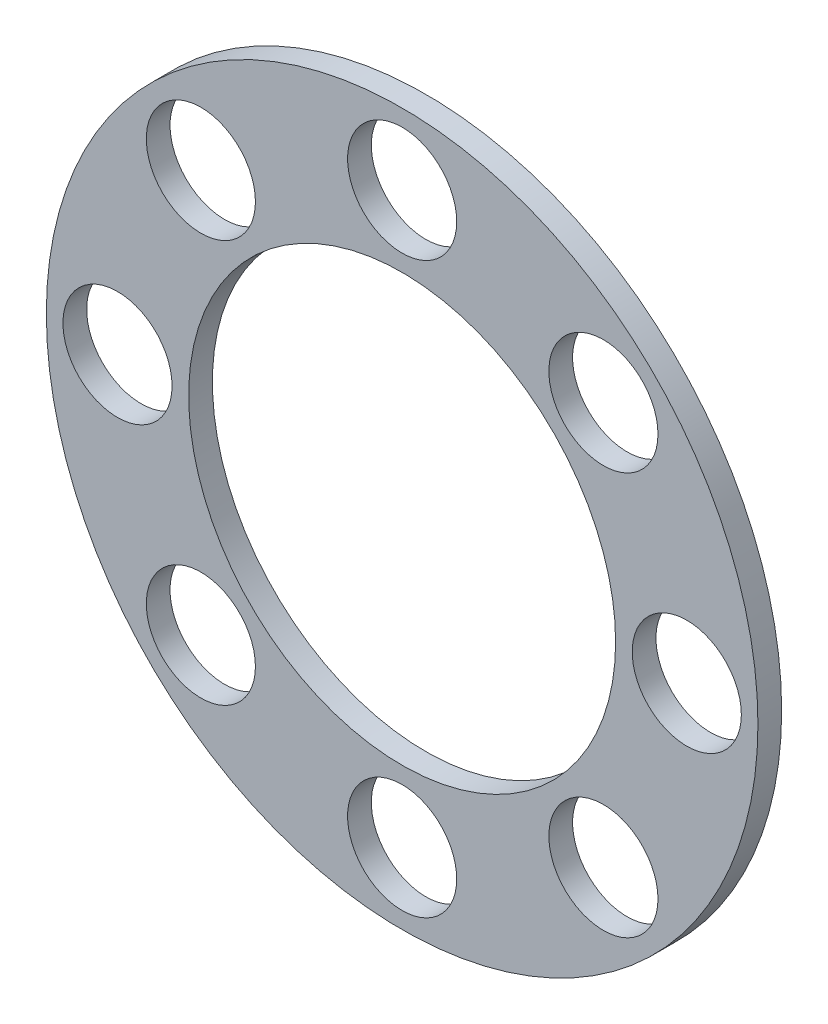
SolidWorks part; units mm, degrees
ref_plane "前视基准面" through (0, 0, 0) normal (0, 0, 1) x (1, 0, 0)
ref_plane "上视基准面" through (0, 0, 0) normal (0, 1, 0) x (1, 0, 0)
ref_plane "右视基准面" through (0, 0, 0) normal (1, 0, 0) x (0, 0, -1)
other "Configuration Table"
sketch "草图1" plane through (0, 0, 0) normal (0, 0, 1) x (1, 0, 0)
  circle A0 centre (0, 0) radius 6 construction
  circle A1 centre (0, 0) radius 7.15 construction
  circle A2 centre (0, 0) radius 4.65 construction
  circle A3 centre (0, 6) radius 1.15
  circle A4 centre (0, 0) radius 7.5
  circle A5 centre (0, 0) radius 4.5
  circle A6 centre (4.2426, 4.2426) radius 1.15
  circle A7 centre (6, 0) radius 1.15
  circle A8 centre (4.2426, -4.2426) radius 1.15
  circle A9 centre (0, -6) radius 1.15
  circle A10 centre (-4.2426, -4.2426) radius 1.15
  circle A11 centre (-6, 0) radius 1.15
  circle A12 centre (-4.2426, 4.2426) radius 1.15
  point P25 (0, 0)
  dimension "D1" = 12
  dimension "D2" = 14.3
  dimension "D3" = 9.3
  dimension "D4" = 15
  dimension "D5" = 9
  dimension "D6" = 8
extrude "凸台-拉伸1" add sketch "草图1" along normal blind 0.5
